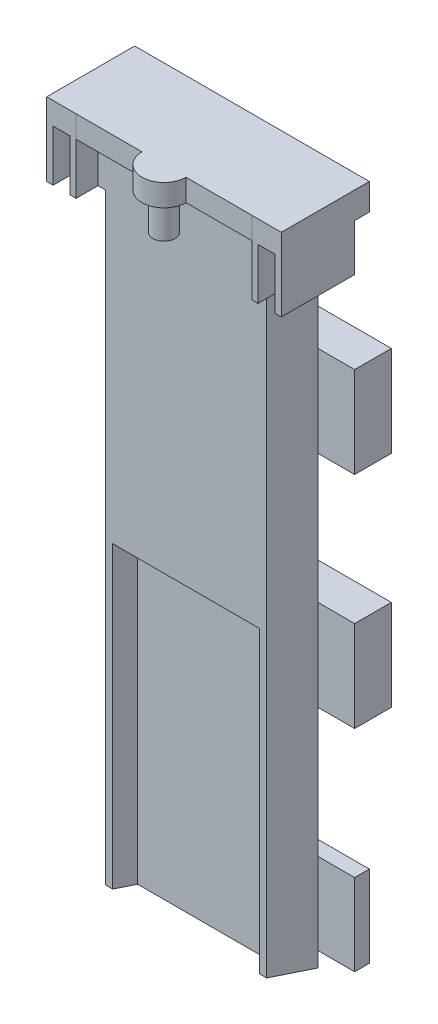
SolidWorks part; units mm, degrees
ref_plane "Front Plane" through (0, 0, 0) normal (0, 0, 1) x (1, 0, 0)
ref_plane "Top Plane" through (0, 0, 0) normal (0, 1, 0) x (1, 0, 0)
ref_plane "Right Plane" through (0, 0, 0) normal (1, 0, 0) x (0, 0, -1)
sketch "Sketch2" plane through (0, 0, 0) normal (0, 0, 1) x (1, 0, 0)
  line L1 (0, 0) -> (-14, 0)
  line L2 (0, 0) -> (0, 48)
  line L3 (0, 48) -> (-14, 48)
  line L4 (-14, 0) -> (-14, 48)
  dimension "D1" = 14
  dimension "D2" = 48
extrude "Boss-Extrude1" add sketch "Sketch2" along normal blind 8
sketch "Sketch3" plane through (0, 0, 0) normal (0, -1, 0) x (-1, 0, 0)
  line L0 (14, 0) -> (12, 0) construction
  line L1 (14, 0) -> (0, 0) construction
  line L2 (0, 0) -> (2, 0) construction
  line L4 (12, 0) -> (2, 0)
  line L5 (12, 0) -> (12, -3.5)
  line L6 (12, -3.5) -> (2, -3.5)
  line L7 (2, 0) -> (2, -3.5)
  dimension "D1" = 2
  dimension "D2" = 2
  dimension "D3" = 3.5
extrude "Cut-Extrude1" cut sketch "Sketch3" against normal through all
sketch "Sketch7" plane through (0, 0, 0) normal (0, -1, 0) x (1, 0, 0)
  line L0 (-14, 0) -> (-13, 0) construction
  line L1 (-14, 0) -> (-12, 0) construction
  line L2 (0, 0) -> (-1, 0) construction
  line L3 (-2, 0) -> (0, 0) construction
  line L4 (-12, 3.5) -> (-13, 3.5) construction
  line L5 (-2, 3.5) -> (-1, 3.5) construction
  line L6 (-1, 3.5) -> (-1, 4.5011) construction
  line L7 (-13, 3.5) -> (-13, 4.5011) construction
  line L8 (-14, 0) -> (-14, 1.0022) construction
  line L9 (-14, 8) -> (-14, 0) construction
  line L10 (0, 0) -> (0, 1.0022) construction
  line L11 (0, 8) -> (0, 0) construction
  line L12 (-14, 1.0022) -> (-13, 1.0022)
  line L13 (-13, 1.0022) -> (-13, 4.5011)
  line L14 (-13, 4.5011) -> (-1, 4.5011)
  line L15 (-1, 4.5011) -> (-1, 1.0022)
  line L16 (-1, 1.0022) -> (0, 1.0022)
  line L17 (0, 1.0022) -> (0, 8)
  line L18 (0, 8) -> (-14, 8)
  line L19 (-14, 8) -> (-14, 1.0022)
  dimension "D1" = 1
extrude "Cut-Extrude4" cut sketch "Sketch7" against normal up to surface (48 mm away) up to face at (-7, 48, 2.875)
sketch "Sketch9" plane through (-13, 0, 0) normal (-1, 0, 0) x (0, 0, 1)
  line L0 (1.0022, 0) -> (4.5011, 1.1592)
  line L1 (4.5011, 48) -> (4.5011, 0) construction
  line L2 (4.5011, 1.1592) -> (4.5011, 0)
  line L3 (4.5011, 0) -> (1.0022, 0)
extrude "Cut-Extrude5" cut sketch "Sketch9" against normal up to surface (12 mm away) up to face at (-1, 24, 2.7516)
sketch "Sketch16" plane through (0, 0, 0) normal (1, 0, 0) x (0, 0, -1)
  line L1 (-1.0022, 48) -> (0, 48)
  line L2 (-1.0022, 48) -> (-1.0022, 0)
  line L3 (-1.0022, 0) -> (0, 0)
  line L4 (0, 48) -> (0, 0)
extrude "Boss-Extrude4" add sketch "Sketch16" along normal blind 1
sketch "Sketch17" plane through (-14, 0, 0) normal (-1, 0, 0) x (0, 0, 1)
  line L1 (0, 48) -> (1.0022, 48)
  line L2 (0, 48) -> (0, 0)
  line L3 (0, 0) -> (1.0022, 0)
  line L4 (1.0022, 48) -> (1.0022, 0)
extrude "Boss-Extrude5" add sketch "Sketch17" along normal blind 1
sketch "Sketch25" plane through (0, 0, 1.0022) normal (0, 0, 1) x (1, 0, 0)
  line L0 (1, 48) -> (1, 0) construction
  line L1 (-1, 48) -> (1, 48)
  line L2 (-1, 48) -> (-1, 43)
  line L3 (-1, 43) -> (1, 43)
  line L4 (1, 48) -> (1, 43)
  line L5 (-13, 48) -> (-13, 1.1592) construction
  line L6 (-15, 48) -> (-13, 48)
  line L7 (-15, 48) -> (-15, 43)
  line L8 (-15, 43) -> (-13, 43)
  line L9 (-13, 48) -> (-13, 43)
  dimension "D1" = 5
extrude "Boss-Extrude10" add sketch "Sketch25" along normal blind 5
sketch "Sketch26" plane through (0, 0, 4.5011) normal (0, 0, 1) x (1, 0, 0)
  line L0 (-1, 48) -> (-1, 43) construction
  line L1 (-13, 48) -> (-1, 48)
  line L2 (-13, 48) -> (-13, 46.5)
  line L3 (-13, 46.5) -> (-1, 46.5)
  line L4 (-1, 48) -> (-1, 46.5)
  dimension "D1" = 1.5
extrude "Boss-Extrude11" add sketch "Sketch26" along normal blind 1.5
sketch "Sketch27" plane through (0, 48, 0) normal (0, 1, 0) x (1, 0, 0)
  line L0 (1, -6.0022) -> (-5.5, -6.0022) construction
  line L2 (-15, -6.0022) -> (-8.5, -6.0011) construction
  line L3 (-1, -6.0011) -> (-13, -6.0011) construction
  circle A2 centre (-7, -6.0011) radius 1.5
  dimension "D1" = 3
  dimension "D2" = 1.5
extrude "Boss-Extrude14" add sketch "Sketch27" against normal blind 1.5
sketch "Sketch29" plane through (0, 48, 0) normal (0, 1, 0) x (1, 0, 0)
  line L0 (-8.5, -6.0011) -> (-5.5, -6.0011) construction
  circle A0 centre (-7, -6.0011) radius 0.75
  dimension "D1" = 1.5
extrude "Cut-Extrude12" cut sketch "Sketch29" against normal blind 1.5
sketch "Sketch30" plane through (0, 0, 6.0022) normal (0, 0, 1) x (1, 0, 0)
  line L0 (-15, 43) -> (-13, 43) construction
  line L1 (-14.56, 43) -> (-13.41, 43)
  line L2 (-14.56, 43) -> (-14.56, 46.49)
  line L3 (-14.56, 46.49) -> (-13.41, 46.49)
  line L4 (-13.41, 43) -> (-13.41, 46.49)
  line L5 (-15, 48) -> (-15, 43) construction
  line L6 (-1, 43) -> (1, 43) construction
  line L7 (-0.59, 43) -> (0.56, 43)
  line L8 (-0.59, 43) -> (-0.59, 46.49)
  line L9 (-0.59, 46.49) -> (0.56, 46.49)
  line L10 (0.56, 43) -> (0.56, 46.49)
  line L11 (1, 43) -> (1, 48) construction
  dimension "D1" = 3.49
  dimension "D2" = 1.15
  dimension "D3" = 0.44
  dimension "D4" = 1.15
  dimension "D5" = 3.49
  dimension "D6" = 0.44
extrude "Cut-Extrude13" cut sketch "Sketch30" against normal up to surface (5 mm away) up to face at (0, 21.5, 1.0022)
sketch "Sketch32" plane through (0, 0, 3.5) normal (0, 0, -1) x (-1, 0, 0)
  line L1 (2, 48) -> (12, 48)
  line L2 (2, 48) -> (2, 0.8276)
  line L3 (2, 0.8276) -> (12, 0.8276)
  line L4 (12, 48) -> (12, 0.8276)
extrude "Boss-Extrude15" add sketch "Sketch32" along normal up to surface (3.5 mm away) up to face at (-13.5, 24, 0)
sketch "Sketch33" plane through (-12, 0, 0) normal (1, 0, 0) x (0, 0, -1)
  line L0 (-3.5, 0.8276) -> (0, 0.8276)
  line L1 (0, 0.8276) -> (0, -0.332)
  line L3 (-3.5, 0.8276) -> (-1.0022, 0) construction
  line L4 (0, -0.332) -> (-3.5, 0.8276)
extrude "Boss-Extrude16" add sketch "Sketch33" along normal up to surface (10 mm away) up to face at (-2, 0.4138, 1.1255)
sketch "Sketch34" plane through (0, 0, 4.5011) normal (0, 0, 1) x (1, 0, 0)
  line L0 (-13, 1.1592) -> (-12, 1.1592) construction
  line L1 (-1, 1.1592) -> (-13, 1.1592) construction
  line L2 (-1, 1.1592) -> (-2, 1.1592) construction
  line L4 (-12, 1.1592) -> (-2, 1.1592)
  line L5 (-12, 1.1592) -> (-12, 21.3592)
  line L6 (-12, 21.3592) -> (-2, 21.3592)
  line L7 (-2, 1.1592) -> (-2, 21.3592)
  dimension "D1" = 1
  dimension "D2" = 20.2
  dimension "D3" = 10
extrude "Cut-Extrude15" cut sketch "Sketch34" against normal blind 1.7
sketch "Sketch35" plane through (0, 1.1592, 0) normal (0, 1, 0) x (1, 0, 0)
  line L1 (-12, -2.8011) -> (-2, -2.8011)
  line L2 (-12, -2.8011) -> (-12, -4.5011)
  line L3 (-12, -4.5011) -> (-2, -4.5011)
  line L4 (-2, -2.8011) -> (-2, -4.5011)
  dimension "D1" = 1.7
extrude "Cut-Extrude16" cut sketch "Sketch35" against normal blind 1
sketch "Sketch38" plane through (1, 0, 0) normal (1, 0, 0) x (0, 0, -1)
  line L6 (0, 0) -> (0, 48) construction
  line L10 (-1.0022, 7.3916) -> (0, 7.3916)
  line L14 (-1.0022, 15.7916) -> (0, 15.7916)
  line L23 (-1.0022, 22.3916) -> (0, 22.3916)
  line L27 (-1.0022, 30.7916) -> (0, 30.7916)
  line L33 (-1.0022, 7.3916) -> (0, 7.3916) construction
  line L36 (-1.0022, 45.7901) -> (0, 45.7901)
  line L40 (-1.0022, 37.3916) -> (0, 37.3916)
  line L46 (-1.0022, 15.7916) -> (0, 15.7916) construction
  line L47 (-1.0022, 22.3916) -> (-1.0022, 30.7916)
  line L49 (-1.0022, 7.3916) -> (-1.0022, 15.7916)
  line L51 (0, 7.3916) -> (0, 15.7916)
  line L52 (0, 22.3916) -> (0, 30.7916)
  line L53 (-1.0022, 37.3916) -> (-1.0022, 45.7901)
  line L54 (0, 45.7901) -> (0, 37.3916)
extrude "Cut-Extrude18" cut sketch "Sketch38" against normal up to surface (16 mm away)
sketch "Sketch40" plane through (-15, 0, 0) normal (-1, 0, 0) x (0, 0, 1)
  line L0 (4.5011, 1.1592) -> (0, -0.332)
  line L1 (0, -0.332) -> (0, 0.468)
  line L2 (0, 7.3916) -> (0, 0) construction
  line L3 (0, 0.468) -> (4.5011, 1.9592)
  line L4 (4.5011, 43) -> (4.5011, 1.1592) construction
  line L5 (4.5011, 1.9592) -> (4.5011, 1.1592)
  dimension "D1" = 0.8
extrude "Cut-Extrude19" cut sketch "Sketch40" against normal blind 20
sketch "Sketch43" plane through (0, 45.7901, 0) normal (0, -1, 0) x (1, 0, 0)
  line L1 (-15, 1.0022) -> (1, 1.0022)
  line L2 (-15, 1.0022) -> (-15, 0)
  line L3 (-15, 0) -> (1, 0)
  line L4 (1, 1.0022) -> (1, 0)
extrude "Cut-Extrude20" cut sketch "Sketch43" against normal blind 0.4
sketch "Sketch44" plane through (0, 30.7916, 0) normal (0, -1, 0) x (-1, 0, 0)
  line L1 (-1, -1.0022) -> (15, -1.0022)
  line L2 (-1, -1.0022) -> (-1, 0)
  line L3 (-1, 0) -> (15, 0)
  line L4 (15, -1.0022) -> (15, 0)
extrude "Cut-Extrude21" cut sketch "Sketch44" against normal blind 0.4
sketch "Sketch45" plane through (0, 15.7916, 0) normal (0, -1, 0) x (1, 0, 0)
  line L1 (-15, 0) -> (1, 0)
  line L2 (-15, 0) -> (-15, 1.0022)
  line L3 (-15, 1.0022) -> (1, 1.0022)
  line L4 (1, 0) -> (1, 1.0022)
extrude "Cut-Extrude22" cut sketch "Sketch45" against normal blind 0.4
sketch "Sketch46" plane through (0, 48, 0) normal (0, 1, 0) x (1, 0, 0)
  circle A0 centre (-7, -6.0011) radius 0.75
extrude "Boss-Extrude18" add sketch "Sketch46" against normal blind 4
sketch "Sketch47" plane through (0, 21.3592, 0) normal (0, -1, 0) x (1, 0, 0)
  line L1 (-12, 4.5011) -> (-2, 4.5011)
  line L2 (-12, 4.5011) -> (-12, 2.8011)
  line L3 (-12, 2.8011) -> (-2, 2.8011)
  line L4 (-2, 4.5011) -> (-2, 2.8011)
extrude "Cut-Extrude23" cut sketch "Sketch47" against normal blind 1
sketch "Sketch48" plane through (-1, 0, 0) normal (1, 0, 0) x (0, 0, -1)
  line L0 (-4.5011, 1.9592) -> (-1.0022, 0.8)
  line L1 (-1.0022, 0.8) -> (-1.0022, 43)
  line L2 (-1.0022, 43) -> (-4.5011, 43)
  line L3 (-4.5011, 43) -> (-4.5011, 1.9592)
extrude "Cut-Extrude24" cut sketch "Sketch48" against normal blind 0.5
sketch "Sketch49" plane through (-13, 0, 0) normal (-1, 0, 0) x (0, 0, 1)
  line L0 (1.0022, 0.8) -> (4.5011, 1.9592)
  line L1 (4.5011, 1.9592) -> (4.5011, 43)
  line L2 (4.5011, 43) -> (1.0022, 43)
  line L3 (1.0022, 43) -> (1.0022, 0.8)
extrude "Cut-Extrude25" cut sketch "Sketch49" against normal blind 0.5
sketch "Sketch50" plane through (1, 0, 0) normal (1, 0, 0) x (0, 0, -1)
  line L0 (-1.0022, 0.8) -> (0, 0.468)
  line L1 (0, 0.468) -> (0, 1.8266)
  line L2 (0, 0.468) -> (0, 7.3916) construction
  line L3 (0, 1.8266) -> (-1.0022, 1.8266)
  line L4 (-1.0022, 0.8) -> (-1.0022, 7.3916) construction
  line L5 (-1.0022, 1.8266) -> (-1.0022, 0.8)
extrude "Cut-Extrude26" cut sketch "Sketch50" against normal through all
sketch "Sketch51" plane through (0, 0, 0) normal (0, 0, -1) x (-1, 0, 0)
  line L1 (-1, 22.3916) -> (15, 22.3916)
  line L2 (-1, 22.3916) -> (-1, 16.1916)
  line L3 (-1, 16.1916) -> (15, 16.1916)
  line L4 (15, 22.3916) -> (15, 16.1916)
  line L5 (-1, 37.3916) -> (15, 37.3916)
  line L6 (-1, 37.3916) -> (-1, 31.1916)
  line L7 (-1, 31.1916) -> (15, 31.1916)
  line L8 (15, 37.3916) -> (15, 31.1916)
extrude "Boss-Extrude19" add sketch "Sketch51" along normal blind 2
sketch "Sketch52" plane through (1, 0, 0) normal (1, 0, 0) x (0, 0, -1)
  line L0 (2, 16.1916) -> (-1.0022, 16.1916) construction
  line L1 (2, 22.3916) -> (1.5, 22.3916)
  line L2 (2, 22.3916) -> (2, 16.1916)
  line L3 (2, 16.1916) -> (1.5, 16.1916)
  line L4 (1.5, 22.3916) -> (1.5, 16.1916)
  dimension "D1" = 0.5
extrude "Cut-Extrude27" cut sketch "Sketch52" against normal up to surface (16 mm away) up to face at (-15, 19.2916, -0.4989)
sketch "Sketch53" plane through (1, 0, 0) normal (1, 0, 0) x (0, 0, -1)
  line L0 (2, 31.1916) -> (-1.0022, 31.1916) construction
  line L1 (2, 37.3916) -> (1.5, 37.3916)
  line L2 (2, 37.3916) -> (2, 31.1916)
  line L3 (2, 31.1916) -> (1.5, 31.1916)
  line L4 (1.5, 37.3916) -> (1.5, 31.1916)
  dimension "D1" = 0.5
extrude "Cut-Extrude28" cut sketch "Sketch53" against normal up to surface (16 mm away) up to face at (-15, 34.2916, -0.4989)
